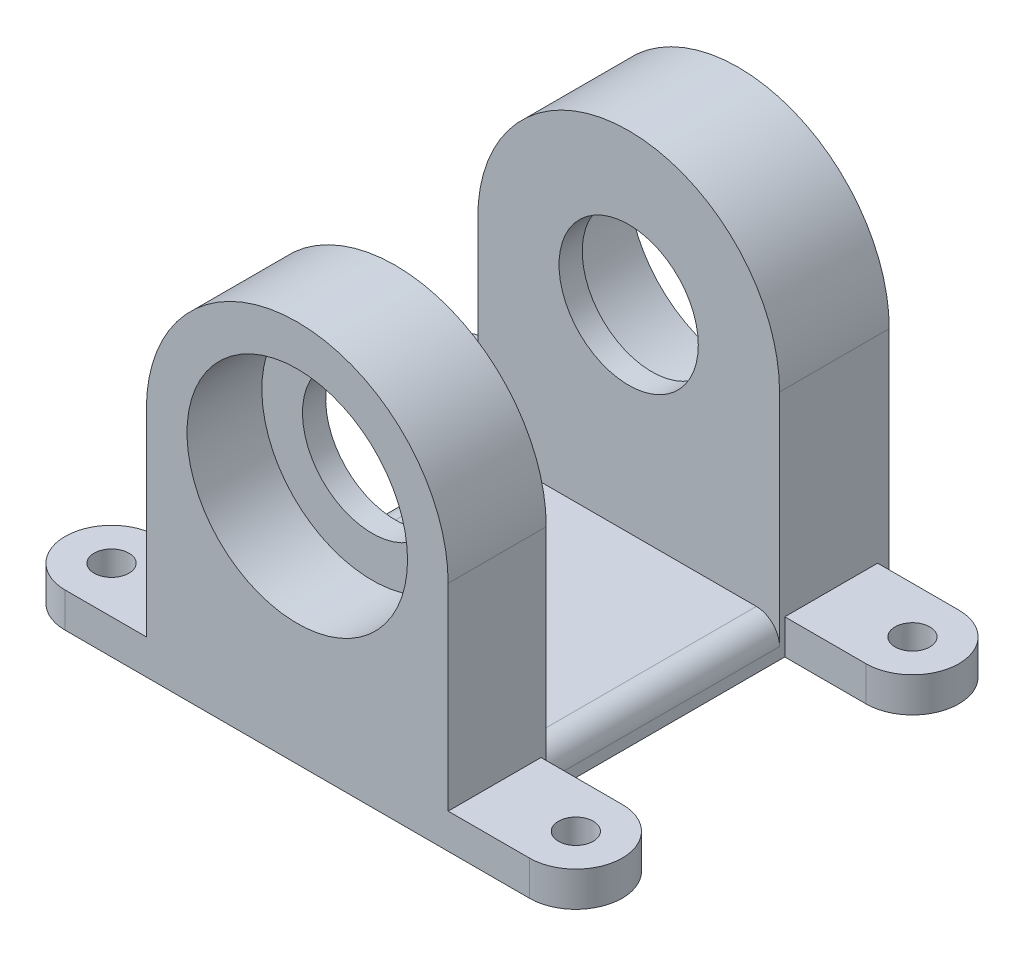
SolidWorks part; units mm, degrees
ref_plane "Alzado" through (0, 0, 0) normal (0, 0, 1) x (1, 0, 0)
ref_plane "Planta" through (0, 0, 0) normal (0, 1, 0) x (1, 0, 0)
ref_plane "Vista lateral" through (0, 0, 0) normal (1, 0, 0) x (0, 0, -1)
sketch "Croquis1" plane through (0, 0, 0) normal (0, 0, 1) x (1, 0, 0)
  line L0 (0, 0) -> (0, 17.6859) construction
  line L1 (0, 0) -> (-25.4426, 0) construction
  line L2 (-13, 0) -> (-13, -20)
  line L3 (-13, -20) -> (13, -20)
  line L4 (13, -20) -> (13, 0)
  circle A0 centre (0, 0) radius 9.5
  arc A1 (13, 0) -> (-13, 0) centre (0, 0) ccw
  dimension "D1" = 19
  dimension "D2" = 13
  dimension "D3" = 20
extrude "Saliente-Extruir1" add sketch "Croquis1" along normal blind 37
sketch "Croquis2" plane through (13, 0, 0) normal (1, 0, 0) x (0, 0, -1)
  line L0 (-18.5, -20) -> (-18.5, -29.3415) construction
  line L1 (-37, -20) -> (0, -20) construction
  line L4 (0, 13) -> (-37, 13) construction
  line L5 (-8.45, 13) -> (-28.55, 13)
  line L7 (-28.55, 13) -> (-28.55, -17)
  line L8 (-28.55, -17) -> (-8.45, -17)
  line L9 (-8.45, -17) -> (-8.45, 13)
  dimension "D1" = 20.1
  dimension "D2" = 3
extrude "Cortar-Extruir2" cut sketch "Croquis2" against normal through all
sketch "Croquis3" plane through (0, 0, 28.55) normal (0, 0, -1) x (-1, 0, 0)
  circle A0 centre (0, 0) radius 9.5
  circle A1 centre (0, 0) radius 6
  dimension "D1" = 19
  dimension "D2" = 12
extrude "Saliente-Extruir2" add sketch "Croquis3" against normal blind 2
sketch "Croquis4" plane through (0, 0, 8.45) normal (0, 0, 1) x (1, 0, 0)
  circle A0 centre (0, 0) radius 9.5 construction
  circle A1 centre (0, 0) radius 9.5
  circle A2 centre (0, 0) radius 6 construction
  circle A3 centre (0, 0) radius 6
extrude "Saliente-Extruir3" add sketch "Croquis4" against normal blind 2
sketch "Croquis5" plane through (0, -20, 0) normal (0, -1, 0) x (1, 0, 0)
  line L0 (13, 37) -> (20, 37)
  line L1 (20, 29) -> (13, 29)
  line L2 (13, 37) -> (13, 0) construction
  line L3 (13, 29) -> (13, 37)
  line L4 (13, 0) -> (20, 0)
  line L5 (20, 8) -> (13, 8)
  line L6 (13, 8) -> (13, 0)
  line L7 (0, 0) -> (0, -17.9347) construction
  line L8 (-13, 0) -> (-20, 0)
  line L9 (-20, 8) -> (-13, 8)
  line L10 (-13, 8) -> (-13, 0)
  line L11 (-13, 29) -> (-13, 37)
  line L12 (-13, 37) -> (-20, 37)
  line L13 (-20, 29) -> (-13, 29)
  arc A0 (20, 37) -> (20, 29) centre (20, 33) cw
  arc A1 (20, 0) -> (20, 8) centre (20, 4) ccw
  arc A2 (-20, 0) -> (-20, 8) centre (-20, 4) cw
  arc A3 (-20, 37) -> (-20, 29) centre (-20, 33) ccw
  dimension "D1" = 7
  dimension "D2" = 4
  dimension "D4" = 4
  dimension "D3" = 7
extrude "Saliente-Extruir4" add sketch "Croquis5" against normal blind 3
sketch "Croquis6" plane through (0, -20, 0) normal (0, -1, 0) x (1, 0, 0)
  circle A0 centre (-20, 33) radius 1.5
  circle A1 centre (20, 33) radius 1.5
  circle A2 centre (-20, 4) radius 1.5
  circle A3 centre (20, 4) radius 1.5
  dimension "D1" = 3
  dimension "D2" = 3
  dimension "D3" = 3
  dimension "D4" = 3
extrude "Cortar-Extruir3" cut sketch "Croquis6" against normal through all
fillet "Redondeo1" [suppressed] radius 3
fillet "Redondeo2" [suppressed] radius 3
fillet "Redondeo3" radius 2 2 edges at (-13, -17, 18.5) (13, -17, 18.5)
sketch "Croquis8" [suppressed] plane through (0, 0, 37) normal (0, 0, 1) x (1, 0, 0)
  line L0 (-13, -20) -> (-13, 0)
  line L1 (-13, 0) -> (-13, -17) construction
  line L2 (13, 0) -> (13, -20)
  line L3 (13, -20) -> (-13, -20)
  arc A0 (13, 0) -> (-13, 0) centre (0, 0) ccw construction
  arc A1 (-13, 0) -> (13, 0) centre (0, 0) cw
ref_plane "Plano1" through (0, 0, 37) normal (0, 0, 1) x (1, 0, 0)
sketch "Croquis9" plane through (0, 0, 0) normal (0, 0, -1) x (-1, 0, 0)
  line L0 (-13, -17) -> (-13, 0)
  line L1 (13, 0) -> (13, -20)
  line L2 (20, -20) -> (-20, -20) construction
  line L3 (13, -20) -> (-13, -20)
  line L4 (-13, -20) -> (-13, -17)
  circle A0 centre (0, 0) radius 9.5
  arc A1 (-13, 0) -> (13, 0) centre (0, 0) cw
  dimension "D1" = 19
extrude "Saliente-Extruir6" add sketch "Croquis9" along normal blind 1
